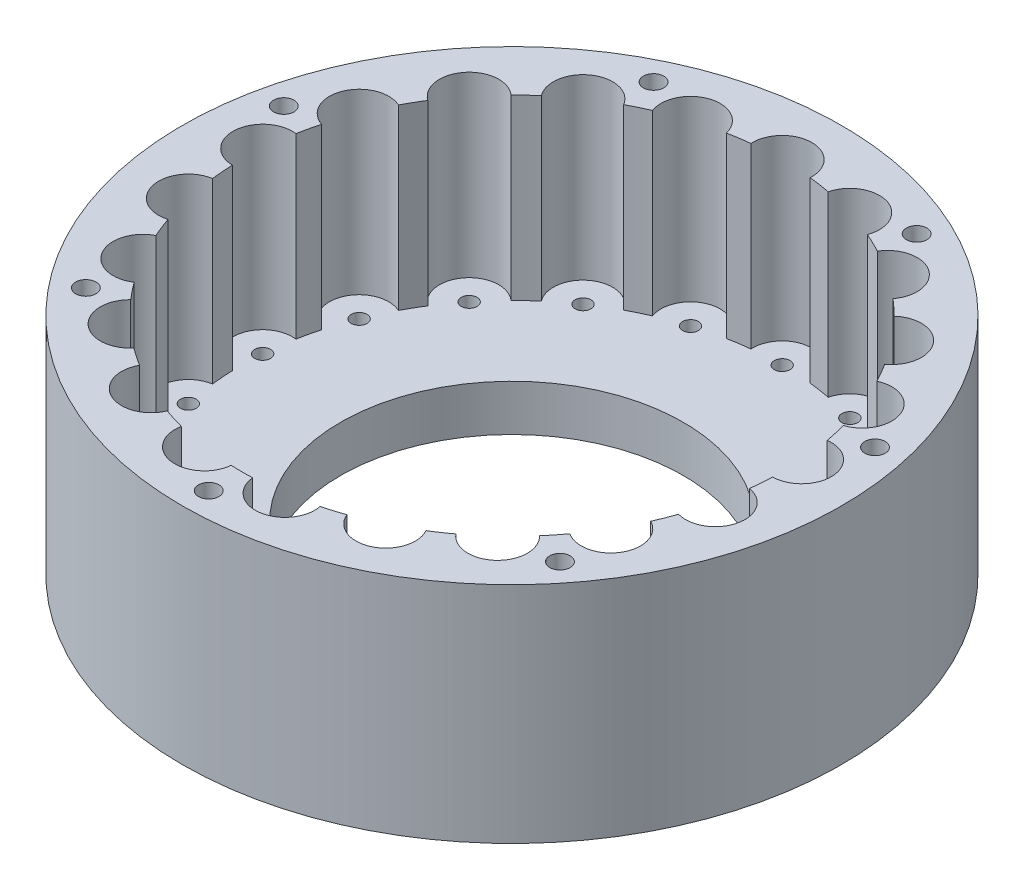
SolidWorks part; units mm, degrees
ref_plane "Ebene vorne" through (0, 0, 0) normal (0, 0, 1) x (1, 0, 0)
ref_plane "Ebene oben" through (0, 0, 0) normal (0, 1, 0) x (1, 0, 0)
ref_plane "Ebene rechts" through (0, 0, 0) normal (1, 0, 0) x (0, 0, -1)
sketch "Skizze1" plane through (0, 0, 0) normal (0, 1, 0) x (1, 0, 0)
  circle A0 centre (0, 0) radius 50
  dimension "D2" = 100
extrude "Aufsatz-Linear austragen1" add sketch "Skizze1" along normal blind 7
sketch "Skizze2" plane through (0, 7, 0) normal (0, 1, 0) x (1, 0, 0)
  circle A0 centre (0, 0) radius 50
  circle A1 centre (0, 0) radius 41
  dimension "D1" = 82
  dimension "D2" = 100
extrude "Aufsatz-Linear austragen2" add sketch "Skizze2" along normal blind 27
sketch "Skizze3" plane through (0, 7, 0) normal (0, 1, 0) x (1, 0, 0)
  circle A0 centre (0, 0) radius 26
  dimension "D1" = 52
extrude "Schnitt-Linear austragen1" cut sketch "Skizze3" against normal blind 27
sketch "Skizze4" plane through (0, 34, 0) normal (0, 1, 0) x (1, 0, 0)
  line L0 (0, 0) -> (0, -50000) construction
  circle A1 centre (0, 41) radius 4.5
  circle A3 centre (0, 0) radius 41 construction
  dimension "D1" = 9
extrude "Schnitt-Linear austragen2" cut sketch "Skizze4" against normal up to surface (27 mm away) up to face at (0, 7, 26)
pattern_circular "Kreismuster1" count 21 over 360 about axis through (0, 0, 0) along (0, 1, 0) of "Schnitt-Linear austragen2"
hole_wizard "Ø2.4 (2.4) Durchmesser Bohrung1" positions "Skizze5" profile "Skizze6" hole size "Ø2.4" standard "ISO" end condition through all
sketch "Skizze5" plane through (0, 7, 0) normal (0, 1, 0) x (1, 0, 0)
  line L0 (0, 0) -> (0, -50000) construction
  point P5 (0, 41)
sketch "Skizze6" plane through (0, 7, -41) normal (1, 0, 0) x (0, 0, 1)
  line L0 (0, 0) -> (0, 7)
  line L1 (0, 7) -> (1.2, 7)
  line L2 (1.2, 7) -> (1.2, 0)
  line L5 (1.2, 0) -> (0, 0)
  line L11 (0, -6.35) -> (0, 107.95) construction
  dimension "Bohrerdurchmesser" = 2.4
  dimension "Bohrungstiefe" = 7
pattern_circular "Kreismuster2" count 21 over 360 about axis through (0, 0, 0) along (0, 1, 0) of "Ø2.4 (2.4) Durchmesser Bohrung1"
hole_wizard "Ø3.1 (3.1) Durchmesser Bohrung1" positions "Skizze7" profile "Skizze8" hole size "Ø3.1" standard "ISO" end condition through all
sketch "Skizze7" plane through (0, 34, 0) normal (0, 1, 0) x (1, 0, 0)
  line L2 (0, 0) -> (0, -50000) construction
  point P10 (0, -46)
  dimension "D1" = 46
sketch "Skizze8" plane through (0, 34, 46) normal (1, 0, 0) x (0, 0, 1)
  line L0 (0, 0) -> (0, 34)
  line L1 (0, 34) -> (1.55, 34)
  line L2 (1.55, 34) -> (1.55, 0)
  line L5 (1.55, 0) -> (0, 0)
  line L11 (0, -6.35) -> (0, 107.95) construction
  dimension "Bohrerdurchmesser" = 3.1
  dimension "Bohrungstiefe" = 34
pattern_circular "Kreismuster3" count 7 over 360 about axis through (0, 0, 0) along (0, 1, 0) of "Ø3.1 (3.1) Durchmesser Bohrung1"
